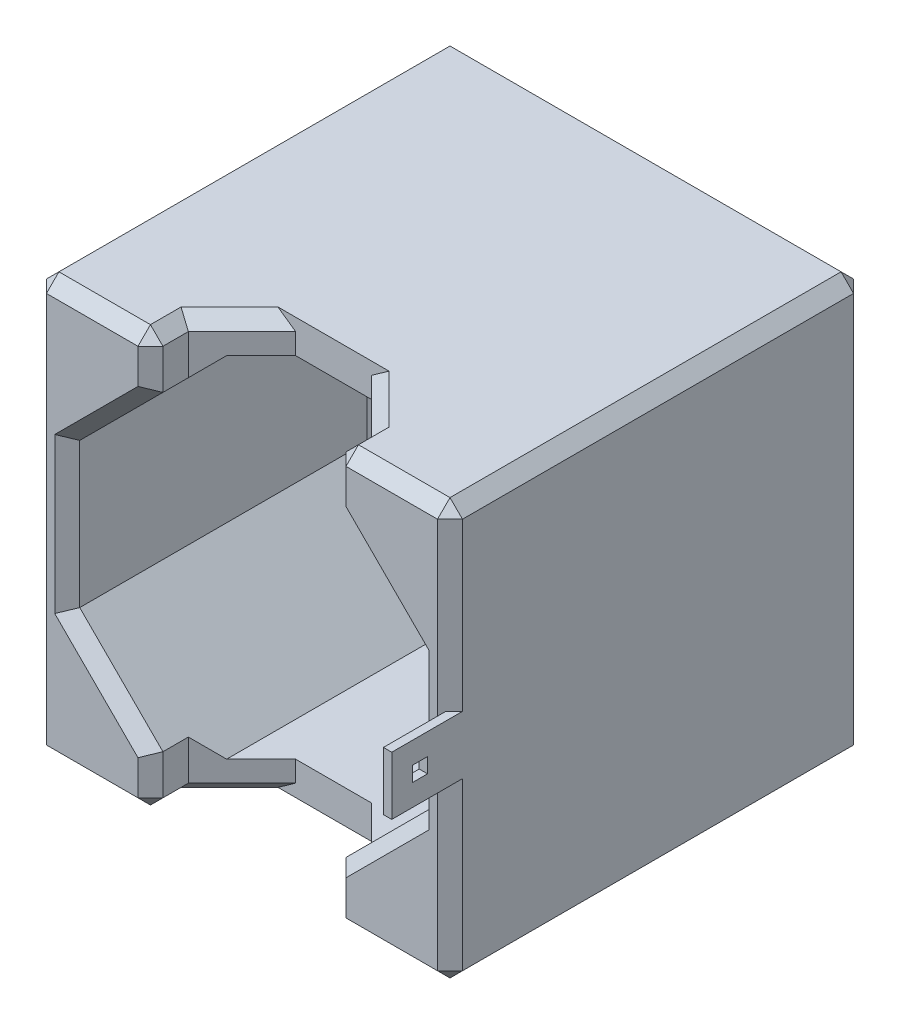
SolidWorks part; units mm, degrees
ref_plane "Front" through (0, 0, 0) normal (0, 0, 1) x (1, 0, 0)
ref_plane "Top" through (0, 0, 0) normal (0, 1, 0) x (1, 0, 0)
ref_plane "Right" through (0, 0, 0) normal (1, 0, 0) x (0, 0, -1)
sketch "Sketch1" plane through (0, 0, 0) normal (0, 0, 1) x (1, 0, 0)
  line L1 (0, 0) -> (50, 0)
  line L2 (0, 0) -> (0, 50)
  line L3 (0, 50) -> (50, 50)
  line L4 (50, 0) -> (50, 50)
  dimension "D1" = 50
extrude "Boss-Extrude1" add sketch "Sketch1" along normal blind 50
sketch "Sketch3" plane through (0, 0, 0) normal (0, -1, 0) x (1, 0, 0)
  line L0 (0, 50) -> (50, 50) construction
  line L7 (14, 61) -> (36, 61) construction
  line L8 (14, 61) -> (14, 39) construction
  line L9 (14, 39) -> (36, 39) construction
  line L10 (36, 61) -> (36, 39) construction
  line L11 (14, 61) -> (36, 39) construction
  line L12 (14, 39) -> (36, 61) construction
  line L16 (29.5563, 39) -> (36, 45.4437)
  line L17 (36, 45.4437) -> (36, 54.5563)
  line L18 (36, 54.5563) -> (29.5563, 61)
  line L19 (29.5563, 61) -> (20.4437, 61)
  line L20 (20.4437, 61) -> (14, 54.5563)
  line L21 (14, 54.5563) -> (14, 45.4437)
  line L22 (14, 45.4437) -> (20.4437, 39)
  line L23 (20.4437, 39) -> (29.5563, 39)
  circle A0 centre (25, 50) radius 11 construction
  point P5 (25, 50)
  dimension "D1" = 22
extrude "Cut-Extrude2" cut sketch "Sketch3" against normal through all
sketch "Sketch4" plane through (0, 0, 50) normal (0, 0, 1) x (1, 0, 0)
  line L0 (25, 50) -> (25, 25) construction
  line L1 (33.6985, 46) -> (16.3015, 46)
  line L2 (16.3015, 46) -> (4, 33.6985)
  line L3 (4, 33.6985) -> (4, 16.3015)
  line L4 (4, 16.3015) -> (16.3015, 4)
  line L5 (16.3015, 4) -> (33.6985, 4)
  line L6 (33.6985, 4) -> (46, 16.3015)
  line L7 (46, 16.3015) -> (46, 33.6985)
  line L8 (46, 33.6985) -> (33.6985, 46)
  line L9 (20.4437, 50) -> (29.5563, 50) construction
  line L10 (25, 25) -> (25, 0) construction
  line L11 (20.4437, 0) -> (29.5563, 0) construction
  circle A0 centre (25, 25) radius 21 construction
  dimension "D1" = 42
extrude "Cut-Extrude3" cut sketch "Sketch4" against normal blind 40
chamfer "Chamfer1" distance 4 angle 45 8 edges at (46, 25, 10) (39.8492, 10.1508, 10) (25, 4, 10) (10.1508, 10.1508, 10) (4, 25, 10) (10.1508, 39.8492, 10) (25, 46, 10) (39.8492, 39.8492, 10)
chamfer "Chamfer3" distance 1.5 angle 45 32 edges at (43, 0, 50) (25, 0, 0) (0, 25, 0) (17.2218, 50, 42.2218) (14, 50, 47.7218) (7, 50, 50) (14, 46.8492, 50) (9, 38.6985, 50) (4, 25, 50) (9, 11.3015, 50) (0, 0, 25) (17.2218, 0, 42.2218) (14, 0, 47.7218) (14, 3.1508, 50) (7, 0, 50) (0, 25, 50) (0, 50, 25) (25, 50, 0) (50, 25, 0) (50, 50, 25) (32.7782, 50, 42.2218) (36, 50, 47.7218) (36, 46.8492, 50) (43, 50, 50) (50, 25, 50) (50, 0, 25) (32.7782, 0, 42.2218) (36, 0, 47.7218) (36, 3.1508, 50) (41, 11.3015, 50) (46, 25, 50) (41, 38.6985, 50)
sketch "Sketch5" plane through (0, 0, 50) normal (0, 0, 1) x (1, 0, 0)
  line L1 (49, 28.5) -> (50, 28.5)
  line L2 (49, 28.5) -> (49, 21.5)
  line L3 (49, 21.5) -> (50, 21.5)
  line L4 (50, 28.5) -> (50, 21.5)
  line L5 (50, 48.5) -> (50, 1.5) construction
  point P8 (50, 25)
  dimension "D1" = 1
  dimension "D2" = 7
extrude "Boss-Extrude2" add sketch "Sketch5" along normal blind 7 and the other way blind 10
sketch "Sketch6" plane through (50, 0, 0) normal (1, 0, 0) x (0, 0, -1)
  line L0 (-54.5, 25) -> (-57, 25) construction
  line L1 (-54.5, 24.1) -> (-52.7, 24.1)
  line L2 (-54.5, 24.1) -> (-54.5, 25.9)
  line L3 (-54.5, 25.9) -> (-52.7, 25.9)
  line L4 (-52.7, 24.1) -> (-52.7, 25.9)
  line L5 (-57, 21.5) -> (-57, 28.5) construction
  dimension "D1" = 2.5
  dimension "D2" = 1.8
extrude "Cut-Extrude4" cut sketch "Sketch6" against normal blind 7
